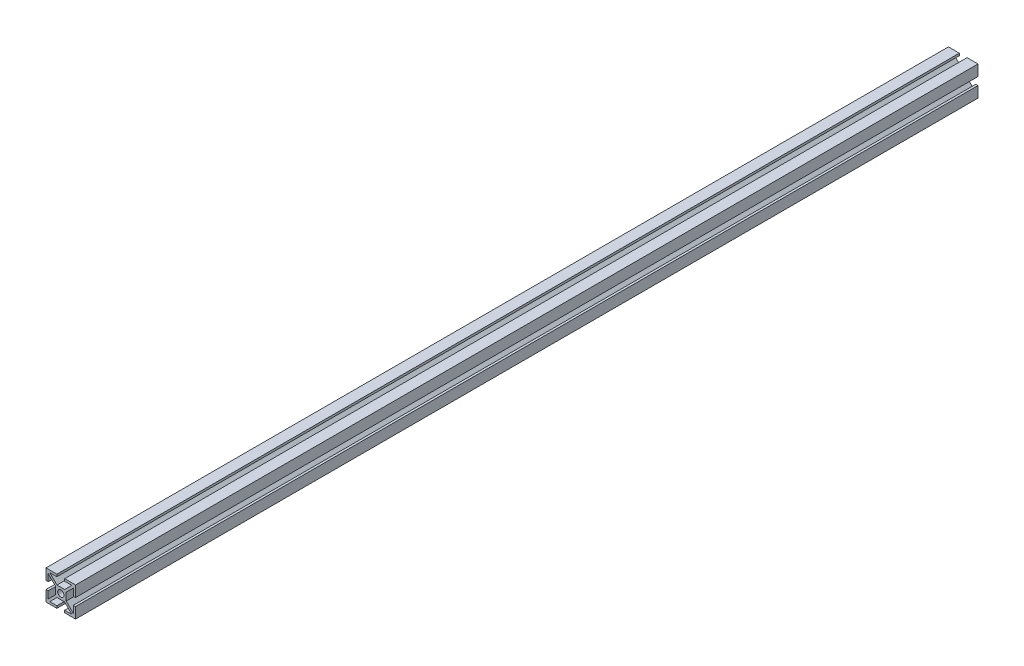
SolidWorks part; units mm, degrees
material "6063-T5"
ref_plane "Front Plane" through (0, 0, 0) normal (0, 0, 1) x (1, 0, 0)
ref_plane "Top Plane" through (0, 0, 0) normal (0, 1, 0) x (1, 0, 0)
ref_plane "Right Plane" through (0, 0, 0) normal (1, 0, 0) x (0, 0, -1)
sketch "Sketch1" plane through (0, 0, 0) normal (0, 0, 1) x (1, 0, 0)
  line L0 (0, 20) -> (20, 0) construction
  line L1 (0, 0) -> (20, 0) construction
  line L2 (0, 0) -> (0, 20) construction
  line L3 (0, 20) -> (20, 20) construction
  line L4 (20, 0) -> (20, 20) construction
  line L5 (20, 20) -> (0, 0) construction
  line L6 (18.5, 1.5) -> (18.5, 0) construction
  line L7 (1.5, 1.5) -> (18.5, 1.5) construction
  line L8 (1.5, 1.5) -> (1.5, 18.5) construction
  line L9 (1.5, 18.5) -> (18.5, 18.5) construction
  line L10 (18.5, 1.5) -> (18.5, 18.5) construction
  line L11 (18.5, 1.5) -> (20, 1.5) construction
  line L12 (6.345, 12.5943) -> (1.5, 17.4393)
  line L13 (13.655, 6.345) -> (6.345, 6.345) construction
  line L14 (13.655, 6.345) -> (13.655, 13.655) construction
  line L15 (13.655, 13.655) -> (6.345, 13.655) construction
  line L16 (6.345, 6.345) -> (6.345, 13.655) construction
  line L17 (7.4057, 13.655) -> (2.5607, 18.5)
  line L18 (2.5607, 18.5) -> (2.0303, 17.9697) construction
  line L19 (2.0303, 17.9697) -> (1.5, 17.4393) construction
  line L20 (6.345, 7.4057) -> (6.345, 12.5943)
  line L21 (12.5943, 13.655) -> (17.4393, 18.5)
  line L22 (17.4393, 18.5) -> (17.9697, 17.9697) construction
  line L23 (17.9697, 17.9697) -> (18.5, 17.4393) construction
  line L24 (18.5, 17.4393) -> (13.655, 12.5943)
  line L25 (13.655, 7.4057) -> (18.5, 2.5607)
  line L26 (18.5, 2.5607) -> (17.9697, 2.0303) construction
  line L27 (17.4393, 1.5) -> (12.5943, 6.345)
  line L28 (7.4057, 6.345) -> (2.5607, 1.5)
  line L29 (17.9697, 2.0303) -> (17.4393, 1.5) construction
  line L30 (1.5, 2.5607) -> (6.345, 7.4057)
  line L31 (2.5607, 1.5) -> (2.0303, 2.0303) construction
  line L32 (2.0303, 2.0303) -> (1.5, 2.5607) construction
  line L33 (7.4057, 13.655) -> (12.5943, 13.655)
  line L34 (13.655, 12.5943) -> (13.655, 7.4057)
  line L36 (12.5943, 6.345) -> (7.4057, 6.345)
  line L37 (0, 10) -> (1.5, 10) construction
  line L38 (0.75, 12.63) -> (0.75, 10) construction
  line L39 (0.75, 10) -> (0.75, 7.37) construction
  line L40 (1.5, 12.63) -> (0, 12.63)
  line L41 (1.5, 7.37) -> (0, 7.37)
  line L42 (10, 1.5) -> (10, 0) construction
  line L43 (10, 0.75) -> (12.63, 0.75) construction
  line L44 (10, 0.75) -> (7.37, 0.75) construction
  line L45 (12.63, 0) -> (12.63, 1.5)
  line L46 (7.37, 1.5) -> (7.37, 0)
  line L47 (18.5, 12.63) -> (20, 12.63)
  line L48 (18.5, 7.37) -> (20, 7.37)
  line L49 (7.37, 20) -> (7.37, 18.5)
  line L50 (12.63, 20) -> (12.63, 18.5)
  line L51 (2.5607, 1.5) -> (7.37, 1.5)
  line L52 (12.63, 1.5) -> (17.4393, 1.5)
  line L53 (18.5, 7.37) -> (18.5, 2.5607)
  line L54 (18.5, 12.63) -> (18.5, 17.4393)
  line L55 (17.4393, 18.5) -> (12.63, 18.5)
  line L56 (7.37, 18.5) -> (2.5607, 18.5)
  line L57 (1.5, 17.4393) -> (1.5, 12.63)
  line L58 (1.5, 7.37) -> (1.5, 2.5607)
  line L59 (7.37, 0) -> (0, 0)
  line L60 (0, 0) -> (0, 7.37)
  line L61 (0, 12.63) -> (0, 20)
  line L62 (0, 20) -> (7.37, 20)
  line L63 (12.63, 20) -> (20, 20)
  line L64 (20, 20) -> (20, 12.63)
  line L65 (20, 7.37) -> (20, 0)
  line L66 (20, 0) -> (12.63, 0)
  circle A0 centre (10, 10) radius 2.095
  dimension "D2" = 4.19
  dimension "D6" = 5.26
  dimension "D1" = 20
  dimension "D3" = 1.5
  dimension "D4" = 3.655
  dimension "D5" = 1.5
extrude "Boss-Extrude1" add sketch "Sketch1" along normal blind 610
